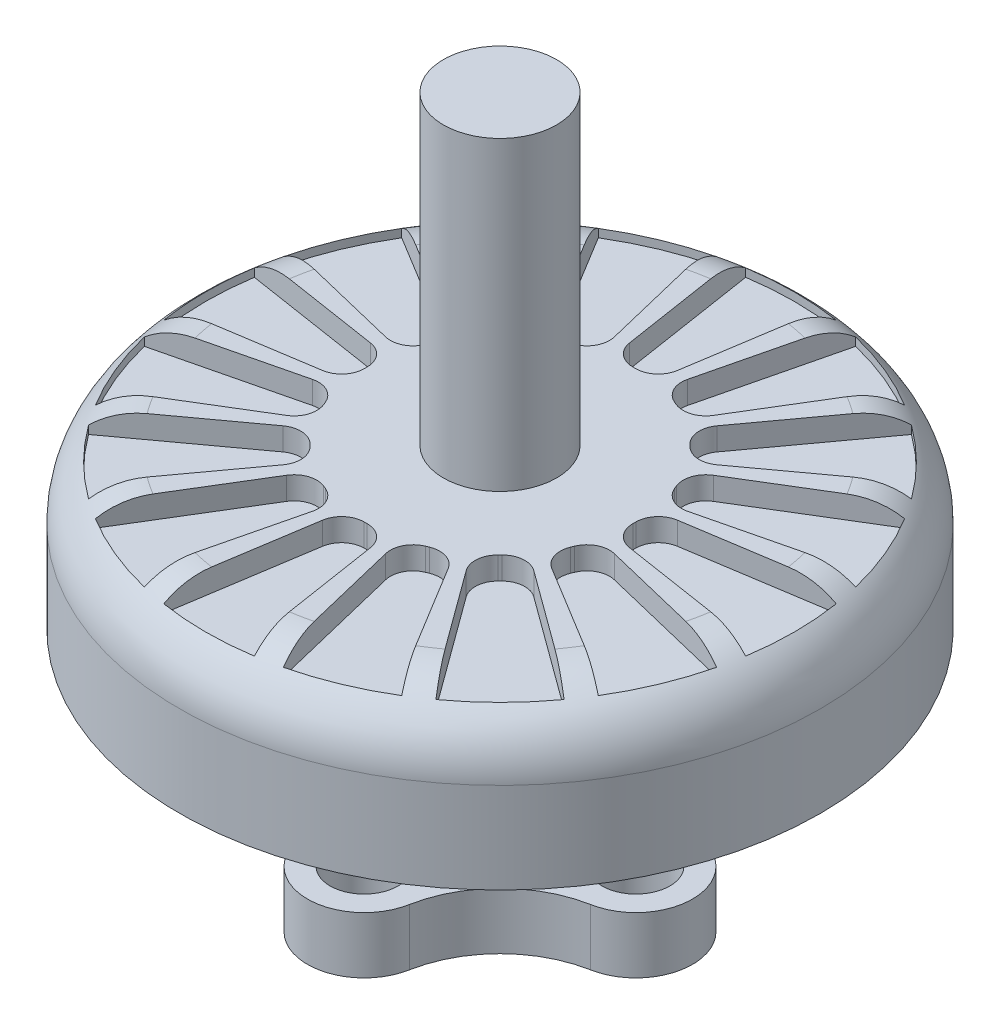
SolidWorks part; units mm, degrees
ref_plane "Front Plane" through (0, 0, 0) normal (0, 0, 1) x (1, 0, 0)
ref_plane "Top Plane" through (0, 0, 0) normal (0, 1, 0) x (1, 0, 0)
ref_plane "Right Plane" through (0, 0, 0) normal (1, 0, 0) x (0, 0, -1)
sketch "Sketch1" plane through (0, 0, 0) normal (0, 1, 0) x (1, 0, 0)
  line L0 (-6, 0) -> (6, 0) construction
  line L1 (0, 6) -> (0, -6) construction
  circle A0 centre (0, 0) radius 6 construction
  circle A1 centre (0, 6) radius 1.5
  circle A2 centre (6, 0) radius 1.5
  circle A3 centre (0, -6) radius 1.5
  circle A4 centre (-6, 0) radius 1.5
  arc A5 (2.4577, 6.4577) -> (-2.4577, 6.4577) centre (0, 6) ccw
  arc A6 (6.4577, -2.4577) -> (6.4577, 2.4577) centre (6, 0) ccw
  arc A7 (-2.4577, -6.4577) -> (2.4577, -6.4577) centre (0, -6) ccw
  arc A8 (-6.4577, 2.4577) -> (-6.4577, -2.4577) centre (-6, 0) ccw
  arc A9 (-6.4577, 2.4577) -> (-2.4577, 6.4577) centre (-7.3732, 7.3732) ccw
  arc A10 (2.4577, 6.4577) -> (6.4577, 2.4577) centre (7.3732, 7.3732) ccw
  arc A11 (6.4577, -2.4577) -> (2.4577, -6.4577) centre (7.3732, -7.3732) ccw
  arc A12 (-2.4577, -6.4577) -> (-6.4577, -2.4577) centre (-7.3732, -7.3732) ccw
  point P14 (0, 0)
  point P22 (0, 0)
  point P36 (0, 0)
  dimension "D1" = 12
  dimension "D2" = 3
  dimension "D4" = 5
  dimension "D6" = 12
  dimension "D7" = 6
  dimension "D8" = 10
  dimension "D3" = 4
  dimension "D5" = 4
  dimension "D9" = 4
extrude "Boss-Extrude2" add sketch "Sketch1" along normal blind 2.5
sketch "Sketch2" plane through (0, 0, 0) normal (0, 0, 1) x (1, 0, 0)
  line L0 (0, -1000) -> (0, 49000) construction
  line L1 (-2.4577, 0) -> (2.4577, 0) construction
  line L2 (-1000, 0) -> (49000, 0) construction
  line L3 (-994.9622, 15.6) -> (49005.0378, 15.6) construction
  line L4 (-994.3429, 29.1) -> (49005.6571, 29.1) construction
  line L5 (0, 29.1) -> (2.5, 29.1)
  line L6 (2.5, 29.1) -> (2.5, 15.6)
  line L7 (2.5, 15.6) -> (14.15, 15.6)
  line L8 (14.15, 15.6) -> (14.15, 8.6)
  line L9 (14.15, 8.6) -> (3.15, 8.6)
  line L10 (3.15, 8.6) -> (4.4, 2.5)
  line L11 (6.4577, 2.5) -> (2.4577, 2.5) construction
  line L12 (4.4, 2.5) -> (0, 2.5)
  line L13 (2.4577, 2.5) -> (-2.4577, 2.5) construction
  line L14 (0, 2.5) -> (0, 29.1)
  point P5 (0, 0)
  dimension "D1" = 15.6
  dimension "D2" = 29.1
  dimension "D3" = 2.5
  dimension "D4" = 14.15
  dimension "D5" = 7
  dimension "D6" = 11
  dimension "D7" = 4.4
revolve "Revolve1" add sketch "Sketch2" angle 360 about L0
fillet "Fillet1" radius 3 1 edges at (14.15, 15.6, 0)
sketch "Sketch4" plane through (0, 15.6, 0) normal (0, 1, 0) x (1, 0, 0)
  line L0 (0, -1000) -> (0, 49000) construction
  line L1 (1.0548, 6.7747) -> (2, 12.8452)
  line L2 (-1.0548, 6.7747) -> (-2, 12.8452)
  line L3 (-0.0667, 5.9286) -> (0.0667, 5.9286)
  line L4 (1.618, 6.6627) -> (3.0679, 12.6328)
  line L5 (2.2071, 5.5028) -> (2.3304, 5.4517)
  line L6 (3.5671, 5.8554) -> (6.7634, 11.1021)
  line L7 (4.0446, 5.5363) -> (7.6687, 10.4972)
  line L8 (4.1449, 4.2393) -> (4.2393, 4.1449)
  line L9 (5.5363, 4.0446) -> (10.4972, 7.6687)
  line L10 (5.8554, 3.5671) -> (11.1021, 6.7634)
  line L11 (5.4517, 2.3304) -> (5.5028, 2.2071)
  line L12 (6.6627, 1.618) -> (12.6328, 3.0679)
  line L13 (6.7747, 1.0548) -> (12.8452, 2)
  line L14 (5.9286, 0.0667) -> (5.9286, -0.0667)
  line L15 (6.7747, -1.0548) -> (12.8452, -2)
  line L16 (6.6627, -1.618) -> (12.6328, -3.0679)
  line L17 (5.5028, -2.2071) -> (5.4517, -2.3304)
  line L18 (5.8554, -3.5671) -> (11.1021, -6.7634)
  line L19 (5.5363, -4.0446) -> (10.4972, -7.6687)
  line L20 (4.2393, -4.1449) -> (4.1449, -4.2393)
  line L21 (4.0446, -5.5363) -> (7.6687, -10.4972)
  line L22 (3.5671, -5.8554) -> (6.7634, -11.1021)
  line L23 (2.3304, -5.4517) -> (2.2071, -5.5028)
  line L24 (1.618, -6.6627) -> (3.0679, -12.6328)
  line L25 (1.0548, -6.7747) -> (2, -12.8452)
  line L26 (0.0667, -5.9286) -> (-0.0667, -5.9286)
  line L27 (-1.0548, -6.7747) -> (-2, -12.8452)
  line L28 (-1.618, -6.6627) -> (-3.0679, -12.6328)
  line L29 (-2.2071, -5.5028) -> (-2.3304, -5.4517)
  line L30 (-3.5671, -5.8554) -> (-6.7634, -11.1021)
  line L31 (-4.0446, -5.5363) -> (-7.6687, -10.4972)
  line L32 (-4.1449, -4.2393) -> (-4.2393, -4.1449)
  line L33 (-5.5363, -4.0446) -> (-10.4972, -7.6687)
  line L34 (-5.8554, -3.5671) -> (-11.1021, -6.7634)
  line L35 (-5.4517, -2.3304) -> (-5.5028, -2.2071)
  line L36 (-6.6627, -1.618) -> (-12.6328, -3.0679)
  line L37 (-6.7747, -1.0548) -> (-12.8452, -2)
  line L38 (-5.9286, -0.0667) -> (-5.9286, 0.0667)
  line L39 (-6.7747, 1.0548) -> (-12.8452, 2)
  line L40 (-6.6627, 1.618) -> (-12.6328, 3.0679)
  line L41 (-5.5028, 2.2071) -> (-5.4517, 2.3304)
  line L42 (-5.8554, 3.5671) -> (-11.1021, 6.7634)
  line L43 (-5.5363, 4.0446) -> (-10.4972, 7.6687)
  line L44 (-4.2393, 4.1449) -> (-4.1449, 4.2393)
  line L45 (-4.0446, 5.5363) -> (-7.6687, 10.4972)
  line L46 (-3.5671, 5.8554) -> (-6.7634, 11.1021)
  line L47 (-2.3304, 5.4517) -> (-2.2071, 5.5028)
  line L48 (-1.618, 6.6627) -> (-3.0679, 12.6328)
  arc A0 (2, 12.8452) -> (-2, 12.8452) centre (0, 0) ccw
  circle A1 centre (0, 0) radius 6 construction
  arc A2 (1.0548, 6.7747) -> (0.0667, 5.9286) centre (0.0667, 6.9286) cw
  arc A3 (-1.0548, 6.7747) -> (-0.0667, 5.9286) centre (-0.0667, 6.9286) ccw
  circle A4 centre (0, 0) radius 13 construction
  arc A5 (6.7634, 11.1021) -> (3.0679, 12.6328) centre (0, 0) ccw
  arc A6 (1.618, 6.6627) -> (2.2071, 5.5028) centre (2.5898, 6.4267) ccw
  arc A7 (3.5671, 5.8554) -> (2.3304, 5.4517) centre (2.7131, 6.3756) cw
  arc A8 (10.4972, 7.6687) -> (7.6687, 10.4972) centre (0, 0) ccw
  arc A9 (4.0446, 5.5363) -> (4.1449, 4.2393) centre (4.8521, 4.9464) ccw
  arc A10 (5.5363, 4.0446) -> (4.2393, 4.1449) centre (4.9464, 4.8521) cw
  arc A11 (12.6328, 3.0679) -> (11.1021, 6.7634) centre (0, 0) ccw
  arc A12 (5.8554, 3.5671) -> (5.4517, 2.3304) centre (6.3756, 2.7131) ccw
  arc A13 (6.6627, 1.618) -> (5.5028, 2.2071) centre (6.4267, 2.5898) cw
  arc A14 (12.8452, -2) -> (12.8452, 2) centre (0, 0) ccw
  arc A15 (6.7747, 1.0548) -> (5.9286, 0.0667) centre (6.9286, 0.0667) ccw
  arc A16 (6.7747, -1.0548) -> (5.9286, -0.0667) centre (6.9286, -0.0667) cw
  arc A17 (11.1021, -6.7634) -> (12.6328, -3.0679) centre (0, 0) ccw
  arc A18 (6.6627, -1.618) -> (5.5028, -2.2071) centre (6.4267, -2.5898) ccw
  arc A19 (5.8554, -3.5671) -> (5.4517, -2.3304) centre (6.3756, -2.7131) cw
  arc A20 (7.6687, -10.4972) -> (10.4972, -7.6687) centre (0, 0) ccw
  arc A21 (5.5363, -4.0446) -> (4.2393, -4.1449) centre (4.9464, -4.8521) ccw
  arc A22 (4.0446, -5.5363) -> (4.1449, -4.2393) centre (4.8521, -4.9464) cw
  arc A23 (3.0679, -12.6328) -> (6.7634, -11.1021) centre (0, 0) ccw
  arc A24 (3.5671, -5.8554) -> (2.3304, -5.4517) centre (2.7131, -6.3756) ccw
  arc A25 (1.618, -6.6627) -> (2.2071, -5.5028) centre (2.5898, -6.4267) cw
  arc A26 (-2, -12.8452) -> (2, -12.8452) centre (0, 0) ccw
  arc A27 (1.0548, -6.7747) -> (0.0667, -5.9286) centre (0.0667, -6.9286) ccw
  arc A28 (-1.0548, -6.7747) -> (-0.0667, -5.9286) centre (-0.0667, -6.9286) cw
  arc A29 (-6.7634, -11.1021) -> (-3.0679, -12.6328) centre (0, 0) ccw
  arc A30 (-1.618, -6.6627) -> (-2.2071, -5.5028) centre (-2.5898, -6.4267) ccw
  arc A31 (-3.5671, -5.8554) -> (-2.3304, -5.4517) centre (-2.7131, -6.3756) cw
  arc A32 (-10.4972, -7.6687) -> (-7.6687, -10.4972) centre (0, 0) ccw
  arc A33 (-4.0446, -5.5363) -> (-4.1449, -4.2393) centre (-4.8521, -4.9464) ccw
  arc A34 (-5.5363, -4.0446) -> (-4.2393, -4.1449) centre (-4.9464, -4.8521) cw
  arc A35 (-12.6328, -3.0679) -> (-11.1021, -6.7634) centre (0, 0) ccw
  arc A36 (-5.8554, -3.5671) -> (-5.4517, -2.3304) centre (-6.3756, -2.7131) ccw
  arc A37 (-6.6627, -1.618) -> (-5.5028, -2.2071) centre (-6.4267, -2.5898) cw
  arc A38 (-12.8452, 2) -> (-12.8452, -2) centre (0, 0) ccw
  arc A39 (-6.7747, -1.0548) -> (-5.9286, -0.0667) centre (-6.9286, -0.0667) ccw
  arc A40 (-6.7747, 1.0548) -> (-5.9286, 0.0667) centre (-6.9286, 0.0667) cw
  arc A41 (-11.1021, 6.7634) -> (-12.6328, 3.0679) centre (0, 0) ccw
  arc A42 (-6.6627, 1.618) -> (-5.5028, 2.2071) centre (-6.4267, 2.5898) ccw
  arc A43 (-5.8554, 3.5671) -> (-5.4517, 2.3304) centre (-6.3756, 2.7131) cw
  arc A44 (-7.6687, 10.4972) -> (-10.4972, 7.6687) centre (0, 0) ccw
  arc A45 (-5.5363, 4.0446) -> (-4.2393, 4.1449) centre (-4.9464, 4.8521) ccw
  arc A46 (-4.0446, 5.5363) -> (-4.1449, 4.2393) centre (-4.8521, 4.9464) cw
  arc A47 (-3.0679, 12.6328) -> (-6.7634, 11.1021) centre (0, 0) ccw
  arc A48 (-3.5671, 5.8554) -> (-2.3304, 5.4517) centre (-2.7131, 6.3756) ccw
  arc A49 (-1.618, 6.6627) -> (-2.2071, 5.5028) centre (-2.5898, 6.4267) cw
  point P12 (0.9231, 5.9286)
  point P15 (-0.9231, 5.9286)
  point P139 (0, 0)
  dimension "D1" = 26
  dimension "D2" = 12
  dimension "D4" = 1
  dimension "D3" = 2
  dimension "D5" = 16
extrude "Cut-Extrude1" cut sketch "Sketch4" against normal mid plane 2
